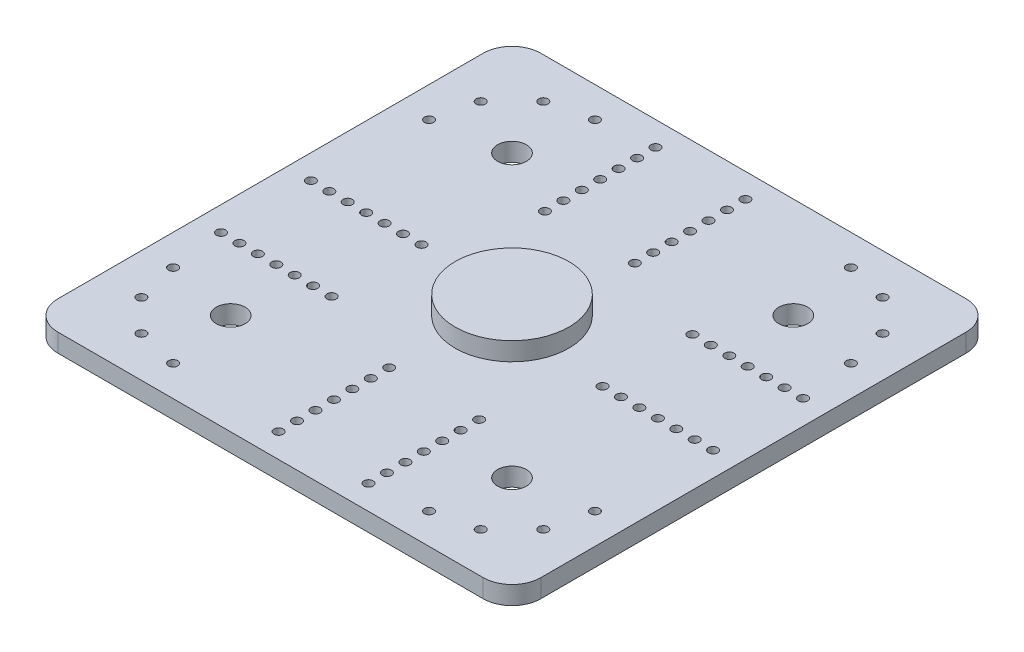
SolidWorks part; units mm, degrees
ref_plane "Front Plane" through (0, 0, 0) normal (0, 0, 1) x (1, 0, 0)
ref_plane "Top Plane" through (0, 0, 0) normal (0, 1, 0) x (1, 0, 0)
ref_plane "Right Plane" through (0, 0, 0) normal (1, 0, 0) x (0, 0, -1)
sketch "Sketch1" plane through (0, 0, 0) normal (0, 1, 0) x (1, 0, 0)
  line L1 (-83.82, 83.82) -> (83.82, 83.82)
  line L2 (-83.82, 83.82) -> (-83.82, -83.82)
  line L3 (-83.82, -83.82) -> (83.82, -83.82)
  line L4 (83.82, 83.82) -> (83.82, -83.82)
  line L5 (-83.82, 83.82) -> (83.82, -83.82) construction
  line L6 (-83.82, -83.82) -> (83.82, 83.82) construction
  point P0 (0, 0)
  dimension "D1" = 167.64
extrude "Boss-Extrude1" add sketch "Sketch1" along normal blind 6.35
sketch "Sketch2" plane through (0, 6.35, 0) normal (0, 1, 0) x (1, 0, 0)
  circle A0 centre (0, 0) radius 19.7258
extrude "Boss-Extrude2" add sketch "Sketch2" along normal blind 6.35
sketch "Sketch3" plane through (0, 6.35, 0) normal (0, 1, 0) x (1, 0, 0)
  line L0 (5.6, 83.82) -> (5.6, -83.82) construction
  line L1 (83.82, 83.82) -> (-83.82, 83.82) construction
  line L2 (-83.82, -83.82) -> (83.82, -83.82) construction
  line L3 (-25.6, 83.82) -> (-25.6, -83.82) construction
  line L4 (5.6, 75.42) -> (-25.6, 75.42) construction
  circle A0 centre (5.6, 75.42) radius 1.6
  circle A1 centre (-25.6, 75.42) radius 1.6
  circle A2 centre (5.6, 69.02) radius 1.6
  circle A3 centre (-25.6, 69.02) radius 1.6
  circle A4 centre (5.6, 62.62) radius 1.6
  circle A5 centre (-25.6, 62.62) radius 1.6
  circle A6 centre (5.6, 56.22) radius 1.6
  circle A7 centre (-25.6, 56.22) radius 1.6
  circle A8 centre (5.6, 49.82) radius 1.6
  circle A9 centre (-25.6, 49.82) radius 1.6
  circle A10 centre (5.6, 43.42) radius 1.6
  circle A11 centre (-25.6, 43.42) radius 1.6
  circle A12 centre (5.6, 37.02) radius 1.6
  circle A13 centre (-25.6, 37.02) radius 1.6
  circle A14 centre (75.42, -5.6) radius 1.6
  circle A15 centre (75.42, 25.6) radius 1.6
  circle A16 centre (69.02, -5.6) radius 1.6
  circle A17 centre (62.62, -5.6) radius 1.6
  circle A18 centre (56.22, -5.6) radius 1.6
  circle A19 centre (49.82, -5.6) radius 1.6
  circle A20 centre (43.42, -5.6) radius 1.6
  circle A21 centre (37.02, -5.6) radius 1.6
  circle A22 centre (69.02, 25.6) radius 1.6
  circle A23 centre (62.62, 25.6) radius 1.6
  circle A24 centre (56.22, 25.6) radius 1.6
  circle A25 centre (49.82, 25.6) radius 1.6
  circle A26 centre (43.42, 25.6) radius 1.6
  circle A27 centre (37.02, 25.6) radius 1.6
  circle A28 centre (-5.6, -75.42) radius 1.6
  circle A29 centre (25.6, -75.42) radius 1.6
  circle A30 centre (-5.6, -69.02) radius 1.6
  circle A31 centre (-5.6, -62.62) radius 1.6
  circle A32 centre (-5.6, -56.22) radius 1.6
  circle A33 centre (-5.6, -49.82) radius 1.6
  circle A34 centre (-5.6, -43.42) radius 1.6
  circle A35 centre (-5.6, -37.02) radius 1.6
  circle A36 centre (25.6, -69.02) radius 1.6
  circle A37 centre (25.6, -62.62) radius 1.6
  circle A38 centre (25.6, -56.22) radius 1.6
  circle A39 centre (25.6, -49.82) radius 1.6
  circle A40 centre (25.6, -43.42) radius 1.6
  circle A41 centre (25.6, -37.02) radius 1.6
  circle A42 centre (-75.42, 5.6) radius 1.6
  circle A43 centre (-75.42, -25.6) radius 1.6
  circle A44 centre (-69.02, 5.6) radius 1.6
  circle A45 centre (-62.62, 5.6) radius 1.6
  circle A46 centre (-56.22, 5.6) radius 1.6
  circle A47 centre (-49.82, 5.6) radius 1.6
  circle A48 centre (-43.42, 5.6) radius 1.6
  circle A49 centre (-37.02, 5.6) radius 1.6
  circle A50 centre (-69.02, -25.6) radius 1.6
  circle A51 centre (-62.62, -25.6) radius 1.6
  circle A52 centre (-56.22, -25.6) radius 1.6
  circle A53 centre (-49.82, -25.6) radius 1.6
  circle A54 centre (-43.42, -25.6) radius 1.6
  circle A55 centre (-37.02, -25.6) radius 1.6
  point P124 (0, 0)
  dimension "D4" = 3.2
  dimension "D1" = 5.6
  dimension "D2" = 8.4
  dimension "D3" = 31.2
  dimension "D5" = 7
  dimension "D6" = 4
extrude "Cut-Extrude1" cut sketch "Sketch3" against normal blind 10
sketch "Sketch5" plane through (0, 6.35, 0) normal (0, 1, 0) x (1, 0, 0)
  line L0 (83.82, 83.82) -> (-83.82, 83.82) construction
  line L1 (-83.82, 83.82) -> (-83.82, -83.82) construction
  circle A0 centre (-69.75, 58.89) radius 1.6
  circle A1 centre (-58.89, 69.75) radius 1.6
  dimension "D2" = 3.2
  dimension "D1" = 14.07
  dimension "D3" = 14.07
  dimension "D4" = 24.93
  dimension "D5" = 24.93
extrude "Cut-Extrude3" cut sketch "Sketch5" against normal through all
pattern_circular "CirPattern2" count 4 over 360 about axis through (0, 0, 0) along (0, 1, 0) of "Cut-Extrude3"
sketch "Sketch6" plane through (0, 6.35, 0) normal (0, 1, 0) x (1, 0, 0)
  line L0 (-83.82, 83.82) -> (-83.82, 33.82) construction
  line L1 (-83.82, 83.82) -> (-83.82, -83.82) construction
  line L2 (-83.82, 33.82) -> (-33.82, 83.82) construction
  line L3 (83.82, 83.82) -> (-83.82, 83.82) construction
  line L4 (-33.82, 83.82) -> (-83.82, 83.82) construction
  circle A0 centre (-44.4266, 73.2134) radius 1.6
  circle A1 centre (-73.2134, 44.4266) radius 1.6
  dimension "D2" = 3.2
  dimension "D1" = 50
  dimension "D3" = 15
  dimension "D4" = 15
extrude "Cut-Extrude4" cut sketch "Sketch6" against normal through all
pattern_circular "CirPattern3" count 4 over 360 about axis through (0, 0, 0) along (0, 1, 0) of "Cut-Extrude4"
sketch "Sketch7" plane through (0, 6.35, 0) normal (0, 1, 0) x (1, 0, 0)
  line L0 (83.82, 83.82) -> (13.82, 83.82) construction
  line L1 (83.82, 83.82) -> (-83.82, 83.82) construction
  line L2 (13.82, 83.82) -> (83.82, 13.82) construction
  line L3 (83.82, -83.82) -> (83.82, 83.82) construction
  line L4 (83.82, 13.82) -> (83.82, 83.82) construction
  circle A0 centre (48.82, 48.82) radius 5
  dimension "D2" = 10
  dimension "D1" = 70
extrude "Cut-Extrude5" cut sketch "Sketch7" against normal through all
pattern_circular "CirPattern4" count 4 over 360 about axis through (0, 0, 0) along (0, 1, 0) of "Cut-Extrude5"
fillet "Fillet1" radius 10 4 edges at (83.82, 3.175, 83.82) (-83.82, 3.175, 83.82) (-83.82, 3.175, -83.82) (83.82, 3.175, -83.82)
